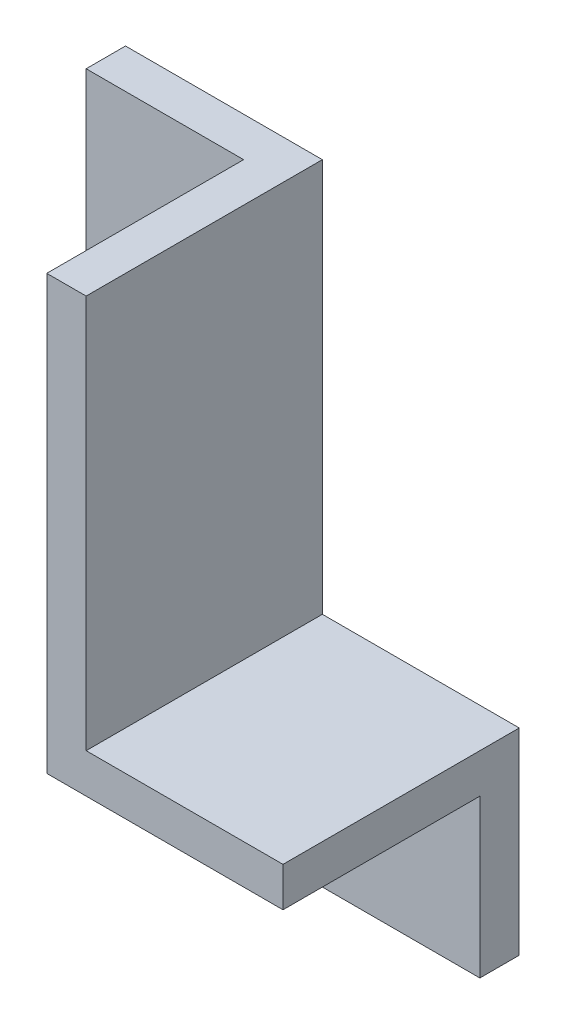
SolidWorks part; units mm, degrees
ref_plane "Front Plane" through (0, 0, 0) normal (0, 0, 1) x (1, 0, 0)
ref_plane "Top Plane" through (0, 0, 0) normal (0, 1, 0) x (1, 0, 0)
ref_plane "Right Plane" through (0, 0, 0) normal (1, 0, 0) x (0, 0, -1)
sketch "Sketch1" plane through (0, 0, 0) normal (0, 0, 1) x (1, 0, 0)
  line L0 (0, 150) -> (50, 150)
  line L1 (0, 0) -> (100, 0)
  line L2 (0, 0) -> (0, 150)
  line L3 (100, 50) -> (100, 0)
  line L5 (50, 150) -> (50, 50)
  line L6 (50, 50) -> (100, 50)
  dimension "D1" = 150
extrude "Boss-Extrude1" add sketch "Sketch1" along normal blind 10
sketch "Sketch2" plane through (0, 0, 10) normal (0, 0, 1) x (1, 0, 0)
  line L0 (40, 150) -> (40, 40)
  line L1 (50, 150) -> (0, 150) construction
  line L2 (40, 40) -> (100, 40)
  line L3 (100, 0) -> (100, 50) construction
  line L4 (100, 40) -> (100, 50)
  line L5 (100, 50) -> (50, 50)
  line L6 (50, 50) -> (50, 150)
  line L7 (50, 150) -> (40, 150)
  dimension "D1" = 10
  dimension "D2" = 10
extrude "Boss-Extrude2" add sketch "Sketch2" along normal blind 50
hole_wizard "CBORE for #10 Binding Head Machine Screw1" positions "Sketch4" profile "Sketch3" counterbore size "#10" standard "ANSI Inch" end condition through all
sketch "Sketch4" plane through (0, 0, 10) normal (0, 0, 1) x (1, 0, 0)
  point P0 (25.4168, 24.243)
sketch "Sketch3" plane through (25.4168, 24.243, 10) normal (1, 0, 0) x (0, -1, 0)
  line L0 (0, 0) -> (0, 10)
  line L1 (0, 10) -> (2.5527, 10)
  line L3 (2.5527, 10) -> (2.5527, 3.1242)
  line L4 (5.5562, 3.1242) -> (2.5527, 3.1242)
  line L5 (5.5562, 3.1242) -> (5.5563, 0.635)
  line L6 (5.5563, 0.635) -> (6.1912, 0)
  line L7 (6.1912, 0) -> (0, 0)
  line L8 (-5.5563, 0.635) -> (-6.1912, 0) construction
  line L11 (0, -6.35) -> (0, 107.95) construction
  dimension "Thru Hole Dia." = 5.1054
  dimension "Thru Hole Depth" = 10
  dimension "C'Bore Dia." = 11.1125
  dimension "C'Bore Depth" = 3.1242
  dimension "Near C'Sink Dia." = 12.3825
  dimension "Near C'Sink Angle" = 90
